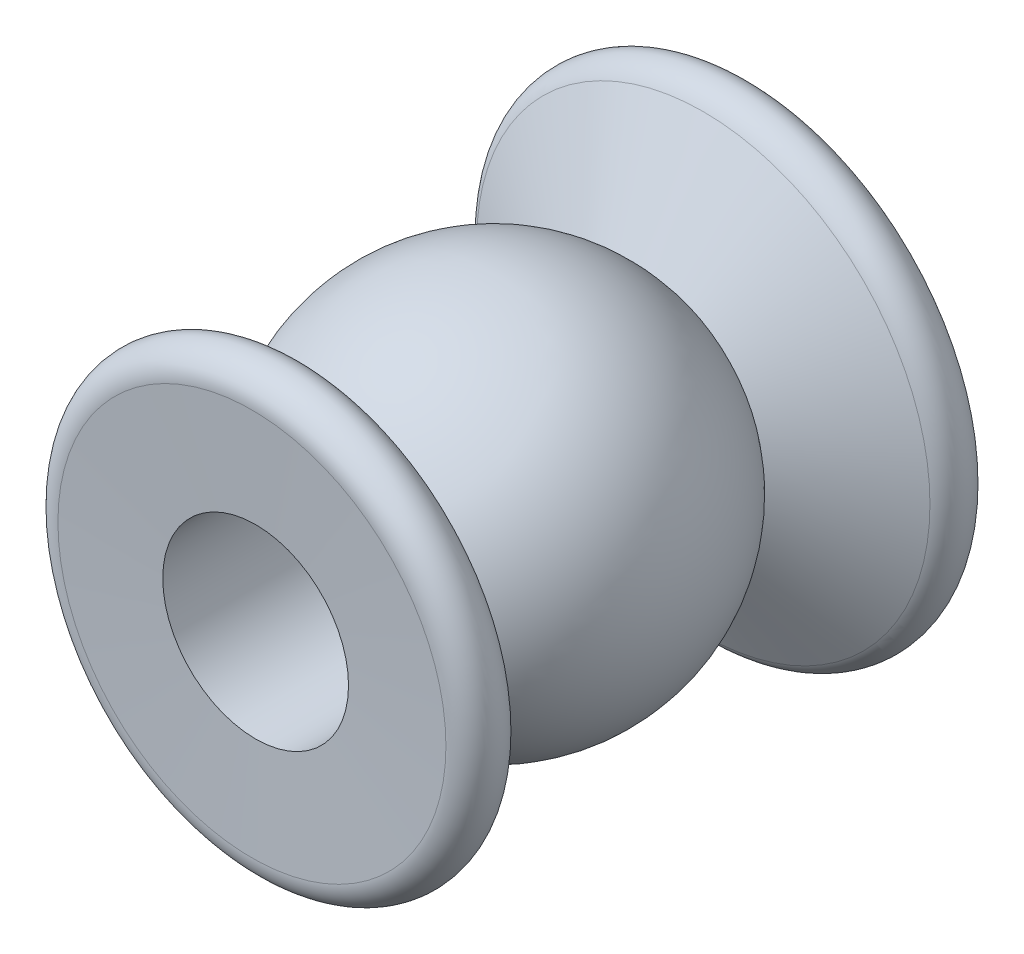
SolidWorks part; units mm, degrees
ref_plane "Front" through (0, 0, 0) normal (0, 0, 1) x (1, 0, 0)
ref_plane "Top" through (0, 0, 0) normal (0, 1, 0) x (1, 0, 0)
ref_plane "Right" through (0, 0, 0) normal (1, 0, 0) x (0, 0, -1)
sketch "草图1" plane through (0, 0, 0) normal (0, 1, 0) x (1, 0, 0)
  line L0 (4.4724, 5.6642) -> (8.5423, 7.8933)
  line L1 (7.9473, 9.7637) -> (0, 8.847)
  line L2 (0, 8.847) -> (0, 3.7435)
  line L3 (0, 0) -> (3.5, 0) construction
  line L4 (0, 8.847) -> (0, 3.7435) construction
  line L5 (0, 0) -> (0, -7.0156) construction
  line L6 (0, 3.7435) -> (4.4724, 5.6642) construction
  line L7 (4.4724, -5.6642) -> (7.7715, -7.21)
  line L8 (7.3106, -9.1149) -> (0, -8.847)
  line L9 (0, -8.847) -> (0, -3.7435)
  line L10 (0, -3.7435) -> (0, 3.7435) construction
  line L11 (0, 3.7435) -> (0, -3.7435)
  arc A1 (4.4724, -5.6642) -> (4.4724, 5.6642) centre (0, 0) ccw
  arc A2 (8.5423, 7.8933) -> (7.9473, 9.7637) centre (8.0619, 8.7703) ccw
  arc A3 (7.7715, -7.21) -> (7.3106, -9.1149) centre (7.3473, -8.1156) cw
  dimension "D1" = 1
  dimension "D2" = 1
ref_axis "基准轴1" through (0, 0, 7.0156) along (0, 0, -1)
revolve "旋转1" add sketch "草图1" angle 360 about axis through (0, 0, 7.0156) along (0, 0, -1)
ref_plane "基准面1" through (0, 0, -9.7637) normal (0, 0, 1) x (1, 0, 0)
sketch "草图2" plane through (0, 0, -9.7637) normal (0, 0, 1) x (1, 0, 0)
  circle A0 centre (0, 0) radius 3.5
extrude "切除-拉伸1" cut sketch "草图2" along normal blind 24
